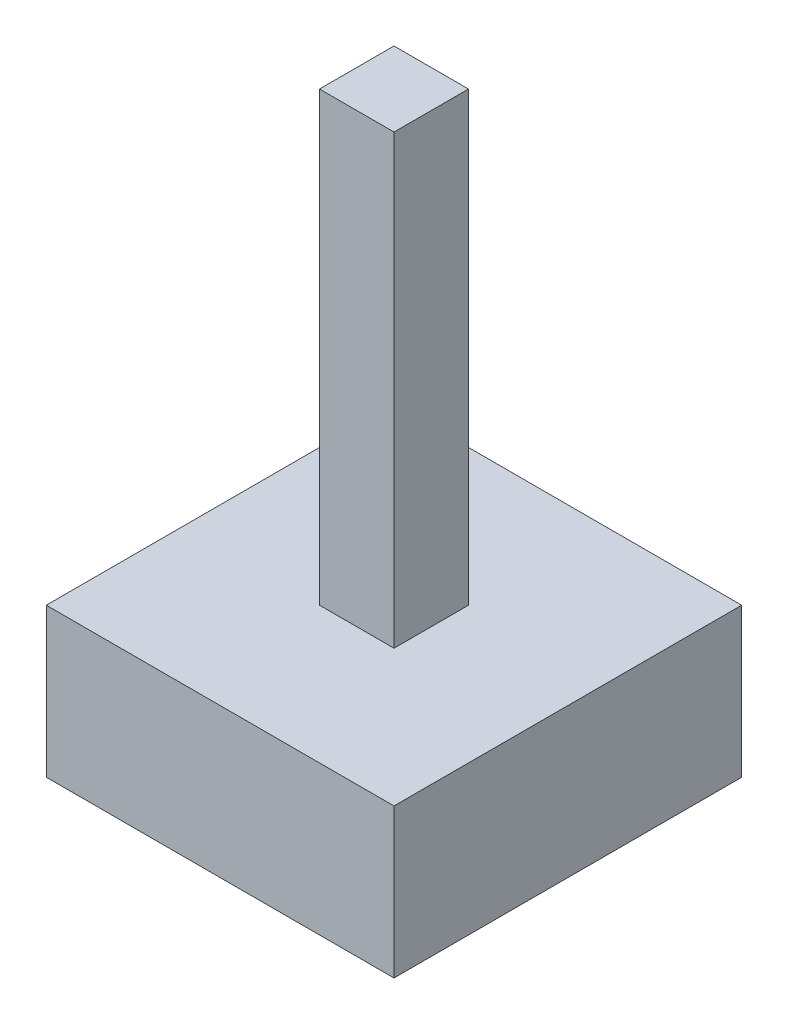
SolidWorks part; units mm, degrees
ref_plane "Front Plane" through (0, 0, 0) normal (0, 0, 1) x (1, 0, 0)
ref_plane "Top Plane" through (0, 0, 0) normal (0, 1, 0) x (1, 0, 0)
ref_plane "Right Plane" through (0, 0, 0) normal (1, 0, 0) x (0, 0, -1)
sketch "Sketch1" plane through (0, 0, 0) normal (0, 1, 0) x (1, 0, 0)
  line L1 (0, 0) -> (8.89, 0)
  line L2 (0, 0) -> (0, 8.89)
  line L3 (0, 8.89) -> (8.89, 8.89)
  line L4 (8.89, 0) -> (8.89, 8.89)
  dimension "D1" = 8.89
extrude "Boss-Extrude1" add sketch "Sketch1" along normal blind 3.81
sketch "Sketch2" plane through (0, 3.81, 0) normal (0, 1, 0) x (1, 0, 0)
  line L0 (4.445, 8.89) -> (4.445, 0) construction
  line L1 (3.4925, 3.4925) -> (5.3975, 3.4925)
  line L2 (3.4925, 3.4925) -> (3.4925, 5.3975)
  line L3 (3.4925, 5.3975) -> (5.3975, 5.3975)
  line L4 (5.3975, 3.4925) -> (5.3975, 5.3975)
  line L5 (8.89, 8.89) -> (0, 8.89) construction
  line L6 (0, 0) -> (8.89, 0) construction
  line L7 (0, 4.445) -> (8.89, 4.445) construction
  line L8 (0, 8.89) -> (0, 0) construction
  line L9 (8.89, 0) -> (8.89, 8.89) construction
  point P16 (5.3975, 4.445)
  point P17 (4.445, 3.4925)
  dimension "D1" = 1.905
  dimension "D2" = 1.905
extrude "Boss-Extrude2" add sketch "Sketch2" along normal blind 11.43
